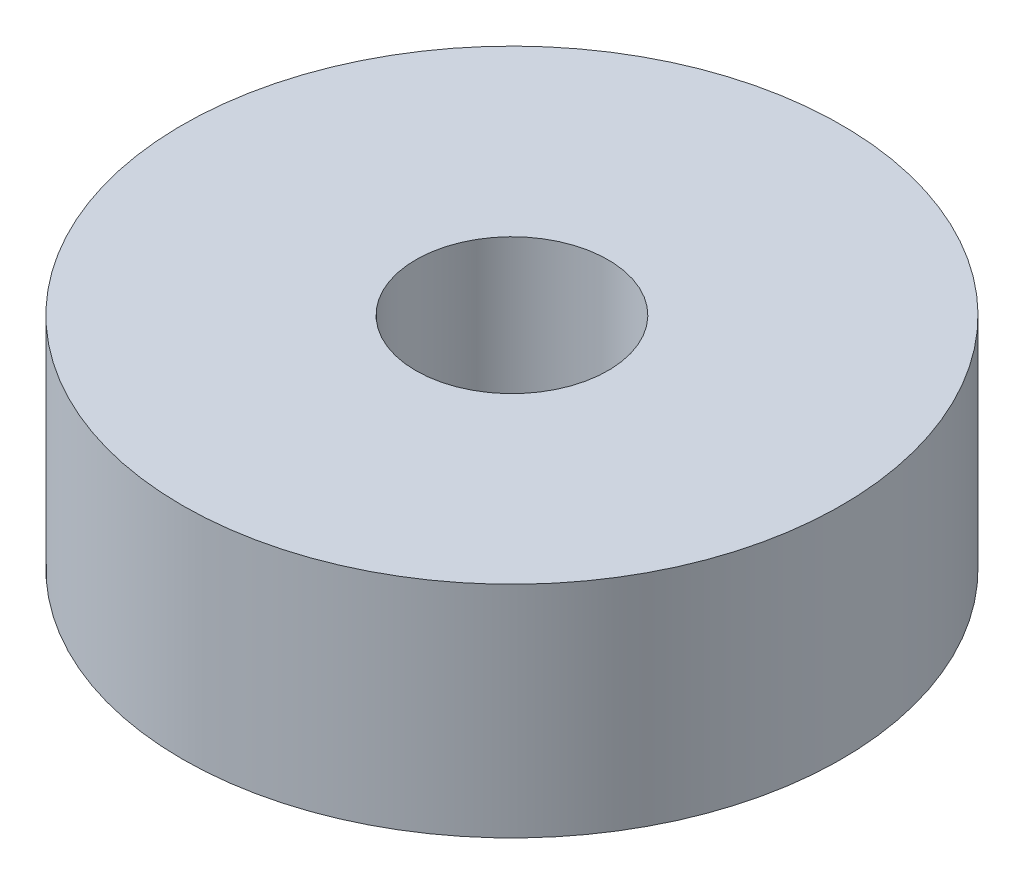
SolidWorks part; units mm, degrees
ref_plane "Front Plane" through (0, 0, 0) normal (0, 0, 1) x (1, 0, 0)
ref_plane "Top Plane" through (0, 0, 0) normal (0, 1, 0) x (1, 0, 0)
ref_plane "Right Plane" through (0, 0, 0) normal (1, 0, 0) x (0, 0, -1)
sketch "Sketch1" plane through (0, 0, 0) normal (0, 1, 0) x (1, 0, 0)
  circle A0 centre (0, 0) radius 1.75
  circle A1 centre (0, 0) radius 6
  dimension "D1" = 3.5
  dimension "D2" = 12
extrude "Boss-Extrude1" add sketch "Sketch1" along normal blind 4
